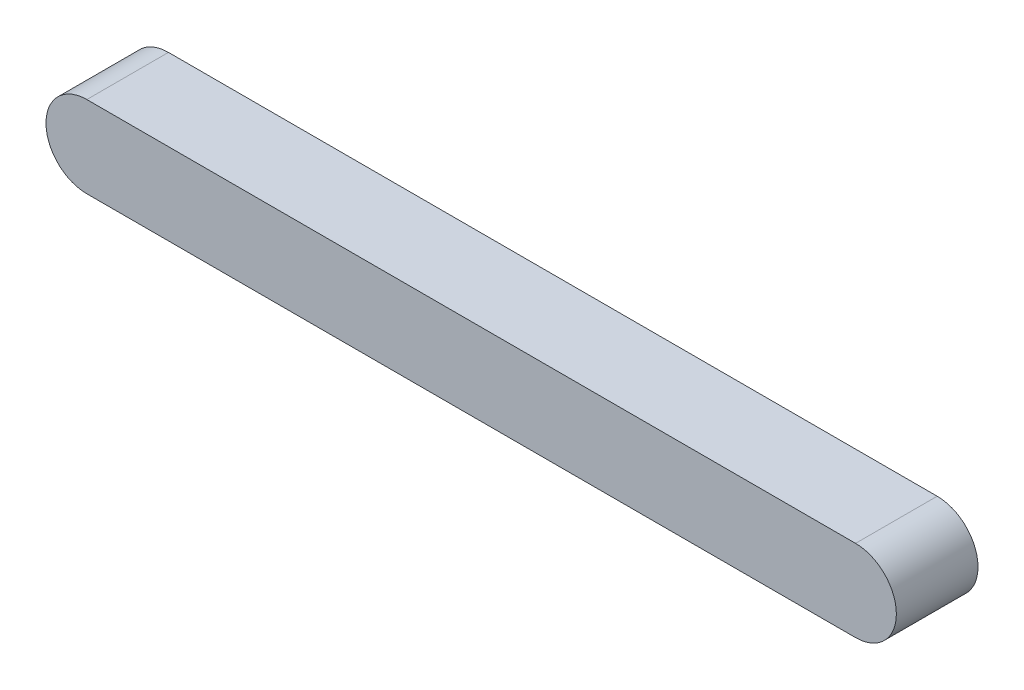
SolidWorks part; units mm, degrees
material "Plain Carbon Steel"
ref_plane "Front Plane" through (0, 0, 0) normal (0, 0, 1) x (1, 0, 0)
ref_plane "Top Plane" through (0, 0, 0) normal (0, 1, 0) x (1, 0, 0)
ref_plane "Right Plane" through (0, 0, 0) normal (1, 0, 0) x (0, 0, -1)
sketch "Sketch1" plane through (0, 0, 0) normal (0, 0, 1) x (1, 0, 0)
  line L0 (-56.5, 0) -> (56.5, 0) construction
  line L1 (-56.5, 6) -> (56.5, 6)
  line L2 (-56.5, -6) -> (56.5, -6)
  line L3 (-40.188, 0) -> (46.724, 0) construction
  line L4 (-62.5, 0) -> (-62.5, 16.5501) construction
  line L5 (62.5, 0) -> (62.5, 15.8403) construction
  arc A0 (-56.5, 6) -> (-56.5, -6) centre (-56.5, 0) ccw
  arc A1 (56.5, -6) -> (56.5, 6) centre (56.5, 0) ccw
  point P2 (0, 0)
  dimension "D2" = 6
  dimension "D1" = 125
extrude "Boss-Extrude1" add sketch "Sketch1" along normal blind 12
